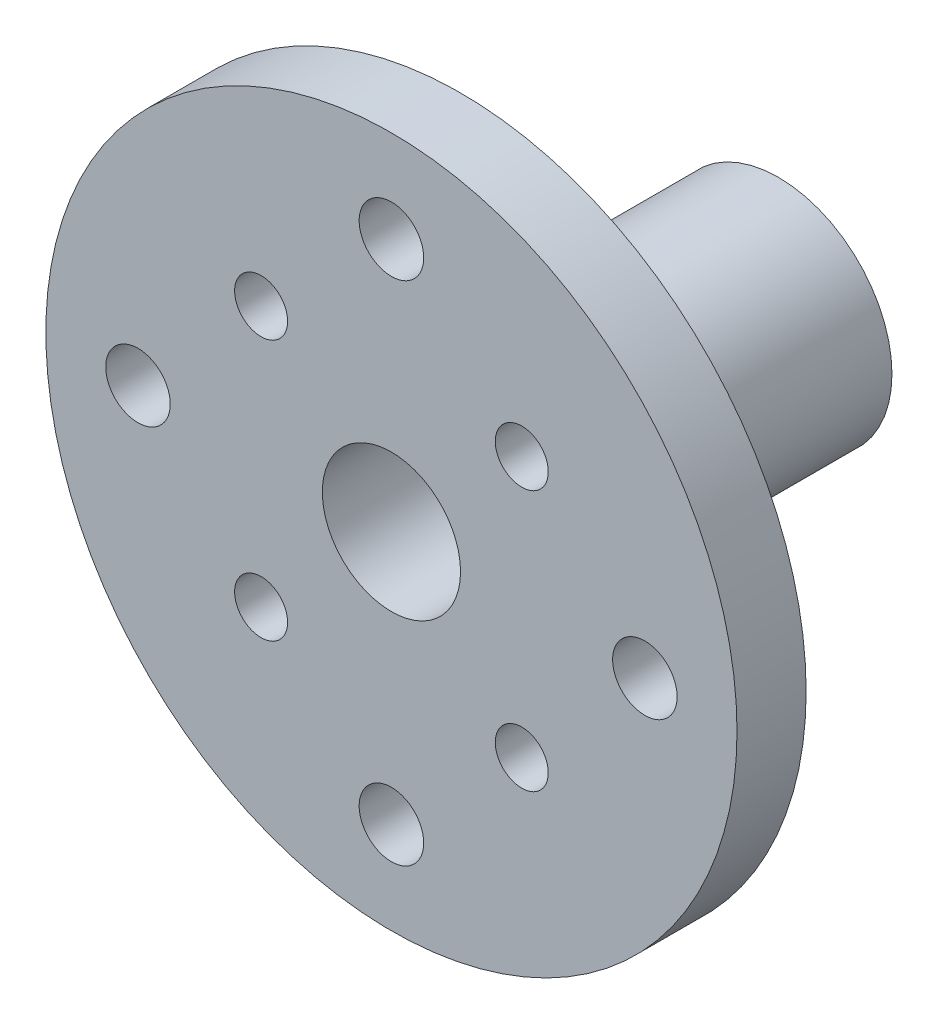
SolidWorks part; units mm, degrees
ref_plane "前视基准面" through (0, 0, 0) normal (0, 0, 1) x (1, 0, 0)
ref_plane "上视基准面" through (0, 0, 0) normal (0, 1, 0) x (1, 0, 0)
ref_plane "右视基准面" through (0, 0, 0) normal (1, 0, 0) x (0, 0, -1)
sketch "草图1" plane through (0, 0, 0) normal (0, 0, 1) x (1, 0, 0)
  circle A0 centre (0, 0) radius 4.925
  circle A1 centre (0, 0) radius 1.55
  dimension "D1" = 9.85
  dimension "D2" = 3.1
extrude "凸台-拉伸1" add sketch "草图1" along normal blind 13.8
sketch "草图2" plane through (0, 0, 13.8) normal (0, 0, 1) x (1, 0, 0)
  line L1 (-11, 0) -> (1.0908, 0) construction
  line L2 (0, 0) -> (-14.696, 14.696) construction
  circle A0 centre (0, 0) radius 15
  circle A1 centre (0, 0) radius 11 construction
  circle A2 centre (-11, 0) radius 1.4
  circle A3 centre (0, 11) radius 1.4
  circle A4 centre (11, 0) radius 1.4
  circle A5 centre (0, -11) radius 1.4
  circle A6 centre (0, 0) radius 8 construction
  circle A7 centre (-5.6569, 5.6569) radius 1.15
  circle A8 centre (5.6569, 5.6569) radius 1.15
  circle A9 centre (5.6569, -5.6569) radius 1.15
  circle A10 centre (-5.6569, -5.6569) radius 1.15
  circle A11 centre (0, 0) radius 1.55
  dimension "D1" = 30
  dimension "D2" = 22
  dimension "D3" = 2.8
  dimension "D5" = 16
  dimension "D6" = 2.3
  dimension "D8" = 8
  dimension "D9" = 8
  dimension "D10" = 45
  dimension "D4" = 4
  dimension "D7" = 4
extrude "凸台-拉伸2" add sketch "草图2" along normal blind 3
sketch "草图3" plane through (0, 0, 16.8) normal (0, 0, 1) x (1, 0, 0)
  circle A0 centre (0, 0) radius 3
  dimension "D1" = 6
extrude "切除-拉伸1" cut sketch "草图3" against normal blind 10
